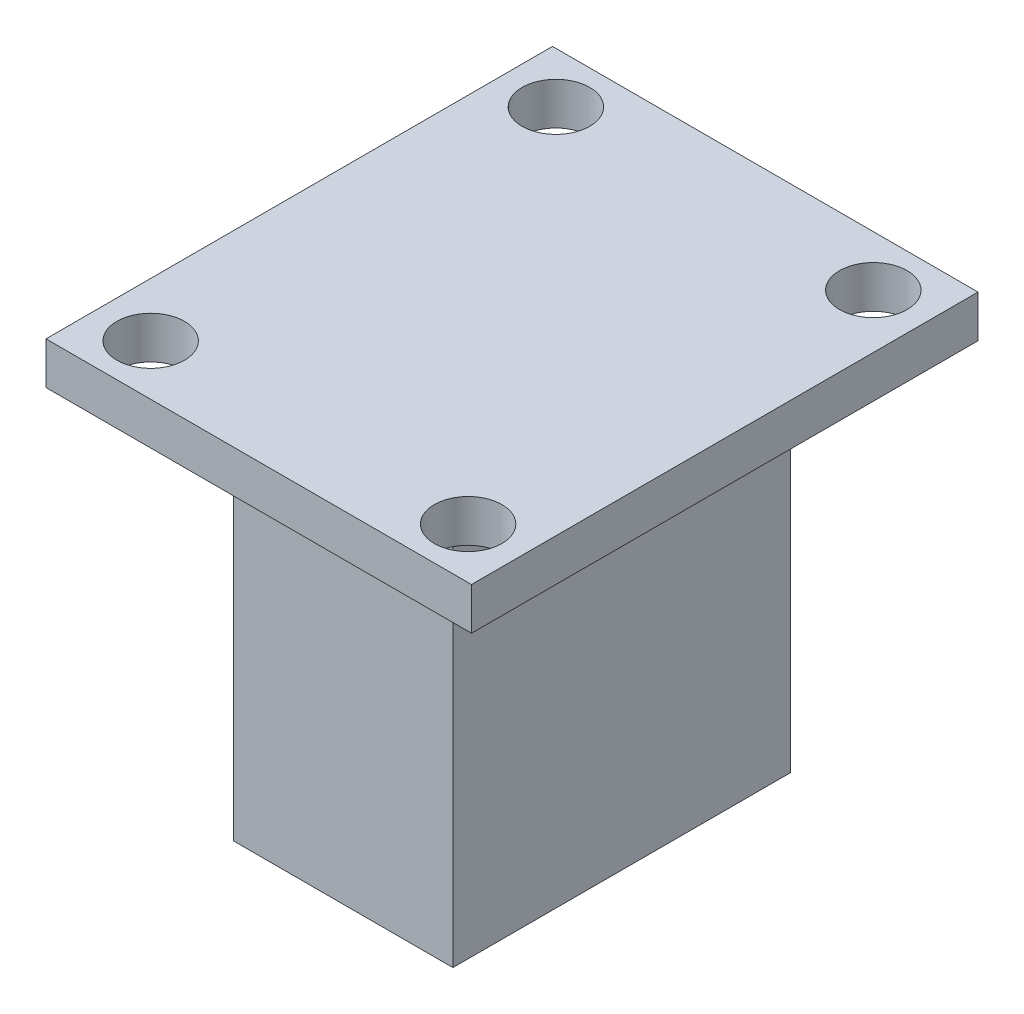
SolidWorks part; units mm, degrees
ref_plane "Front Plane" through (0, 0, 0) normal (0, 0, 1) x (1, 0, 0)
ref_plane "Top Plane" through (0, 0, 0) normal (0, 1, 0) x (1, 0, 0)
ref_plane "Right Plane" through (0, 0, 0) normal (1, 0, 0) x (0, 0, -1)
sketch "Sketch3" plane through (0, 0, 0) normal (0, 1, 0) x (1, 0, 0)
  line L1 (16.002, -19.05) -> (-16.002, -19.05)
  line L2 (16.002, -19.05) -> (16.002, 19.05)
  line L3 (16.002, 19.05) -> (-16.002, 19.05)
  line L4 (-16.002, -19.05) -> (-16.002, 19.05)
  line L5 (16.002, -19.05) -> (-16.002, 19.05) construction
  line L6 (16.002, 19.05) -> (-16.002, -19.05) construction
  point P0 (0, 0)
  dimension "D1" = 32.004
  dimension "D2" = 38.1
extrude "Boss-Extrude1" add sketch "Sketch3" against normal blind 3.175
sketch "Sketch4" plane through (0, 0, 0) normal (0, 1, 0) x (1, 0, 0)
  line L1 (11.938, 15.24) -> (-11.938, 15.24) construction
  line L2 (11.938, 15.24) -> (11.938, -15.24) construction
  line L3 (11.938, -15.24) -> (-11.938, -15.24) construction
  line L4 (-11.938, 15.24) -> (-11.938, -15.24) construction
  line L5 (11.938, 15.24) -> (-11.938, -15.24) construction
  line L6 (11.938, -15.24) -> (-11.938, 15.24) construction
  circle A0 centre (11.938, 15.24) radius 2.54
  circle A1 centre (-11.938, 15.24) radius 2.54
  circle A2 centre (-11.938, -15.24) radius 2.54
  circle A3 centre (11.938, -15.24) radius 2.54
  point P0 (0, 0)
  dimension "D3" = 5.08
  dimension "D1" = 30.48
  dimension "D2" = 23.876
extrude "Screw Holes" cut sketch "Sketch4" against normal through all
sketch "Sketch5" plane through (0, 0, 0) normal (0, 1, 0) x (1, 0, 0)
  line L1 (8.255, 12.7) -> (-8.255, 12.7)
  line L2 (8.255, 12.7) -> (8.255, -12.7)
  line L3 (8.255, -12.7) -> (-8.255, -12.7)
  line L4 (-8.255, 12.7) -> (-8.255, -12.7)
  line L5 (8.255, 12.7) -> (-8.255, -12.7) construction
  line L6 (8.255, -12.7) -> (-8.255, 12.7) construction
  point P0 (0, 0)
  dimension "D1" = 25.4
  dimension "D2" = 16.51
extrude "Wheel Approx" add sketch "Sketch5" against normal blind 32.004
